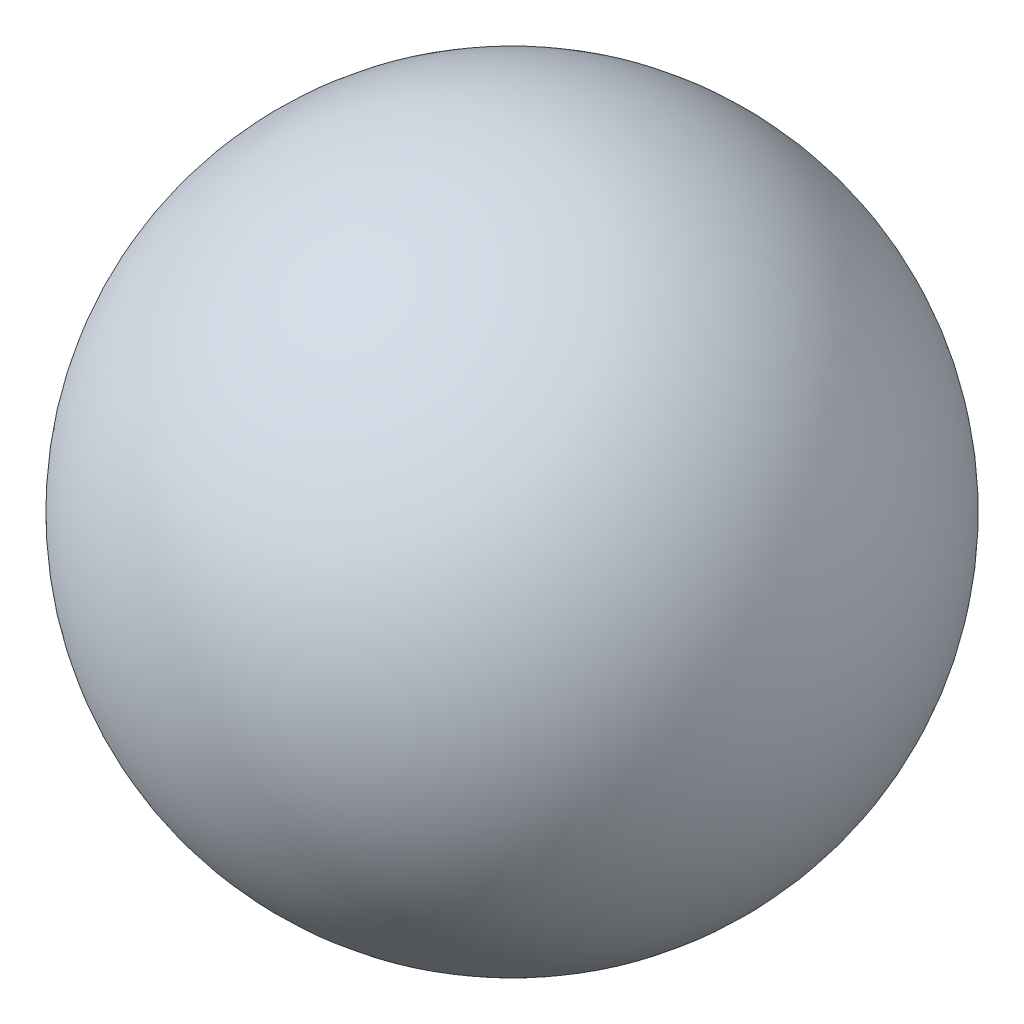
SolidWorks part; units mm, degrees
ref_plane "Front Plane" through (0, 0, 0) normal (0, 0, 1) x (1, 0, 0)
ref_plane "Top Plane" through (0, 0, 0) normal (0, 1, 0) x (1, 0, 0)
ref_plane "Right Plane" through (0, 0, 0) normal (1, 0, 0) x (0, 0, -1)
sketch "Sketch1" plane through (0, 0, 0) normal (0, 0, 1) x (1, 0, 0)
  line L0 (0, 4) -> (0, -4)
  arc A0 (0, 4) -> (0, -4) centre (0, 0) ccw
  dimension "D1" = 8
revolve "Revolve1" add sketch "Sketch1" angle 360 about L0
